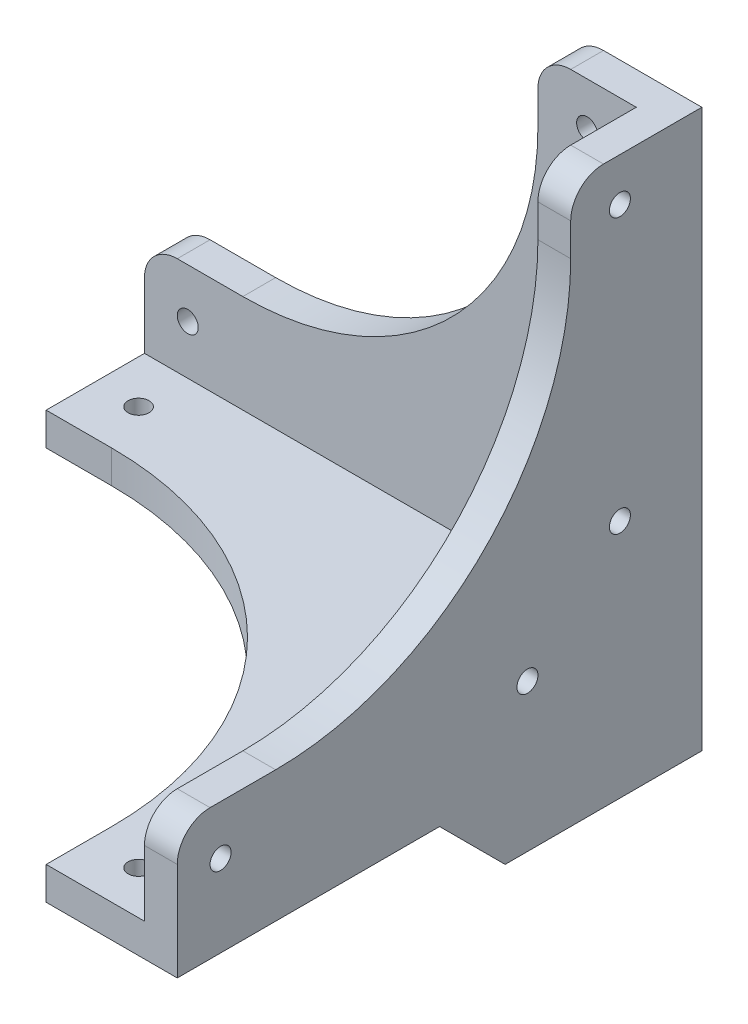
SolidWorks part; units mm, degrees
ref_plane "Front Plane" through (0, 0, 0) normal (0, 0, 1) x (1, 0, 0)
ref_plane "Top Plane" through (0, 0, 0) normal (0, 1, 0) x (1, 0, 0)
ref_plane "Right Plane" through (0, 0, 0) normal (1, 0, 0) x (0, 0, -1)
sketch "Sketch1" plane through (0, 0, 0) normal (0, 1, 0) x (1, 0, 0)
  line L1 (-50, 0) -> (-60, 0)
  line L3 (15, 15) -> (-60, 15)
  line L4 (-60, 0) -> (-60, 15)
  line L5 (-1037.2149, 7.5) -> (48962.7851, 7.5) construction
  line L6 (0, -50) -> (0, -60)
  line L7 (0, -60) -> (15, -60)
  line L8 (15, 15) -> (15, -60)
  line L9 (7.5, -1028.6065) -> (7.5, 48971.3935) construction
  arc A0 (-50, 0) -> (0, -50) centre (-50, -50) cw
  circle A1 centre (7.5, 7.5) radius 1.6
  circle A2 centre (7.5, -6.6) radius 1.6
  circle A3 centre (7.5, -53.4) radius 1.6
  circle A4 centre (-53.4, 7.5) radius 1.6
  circle A5 centre (-6.6, 7.5) radius 1.6
  point P14 (0, 0)
  dimension "D7" = 50
  dimension "D8" = 3.2
  dimension "D9" = 5
  dimension "D10" = 5
  dimension "D11" = 5
  dimension "D12" = 5
  dimension "D2" = 15
  dimension "D3" = 75
  dimension "D4" = 75
  dimension "D5" = 15
extrude "Boss-Extrude1" add sketch "Sketch1" along normal blind 5
sketch "Sketch2" plane through (15, 0, 0) normal (1, 0, 0) x (0, 0, -1)
  line L0 (-1069.6661, 12.5) -> (48930.3339, 12.5) construction
  line L1 (-60, 0) -> (15, 0) construction
  line L2 (-10, -10) -> (-20, 0)
  line L3 (-60, 5) -> (15, 5) construction
  line L4 (15, 5) -> (15, 0) construction
  line L5 (-10, -10) -> (15, -10)
  line L6 (-60, 0) -> (-60, 15)
  line L7 (5, 75) -> (15, 75)
  line L8 (15, -10) -> (15, 75)
  line L9 (-60, 5) -> (-60, 0) construction
  line L10 (-20, 0) -> (-60, 0)
  line L11 (7.5, -1006.2083) -> (7.5, 48993.7917) construction
  line L13 (-55, 20) -> (-45, 20)
  line L14 (0, 70) -> (0, 65)
  circle A0 centre (-53.4, 12.5) radius 1.6
  circle A1 centre (-6.6, 12.5) radius 1.6
  circle A2 centre (7.5, 26.6) radius 1.6
  circle A3 centre (7.5, 68.4) radius 1.6
  arc A4 (-60, 15) -> (-55, 20) centre (-55, 15) cw
  arc A5 (5, 75) -> (0, 70) centre (5, 70) ccw
  arc A6 (-45, 20) -> (0, 65) centre (-45, 65) ccw
  dimension "D8" = 3.2
  dimension "D9" = 5
  dimension "D10" = 5
  dimension "D11" = 5
  dimension "D12" = 5
  dimension "D13" = 5
  dimension "D4" = 5
  dimension "D14" = 45
  dimension "D1" = 10
  dimension "D2" = 70
  dimension "D3" = 15
  dimension "D5" = 15
  dimension "D6" = 25
  dimension "D7" = 45
extrude "Boss-Extrude2" add sketch "Sketch2" along normal blind 5
sketch "Sketch3" plane through (0, 0, -15) normal (0, 0, -1) x (-1, 0, 0)
  line L0 (-20, -10) -> (10, -10)
  line L1 (10, -10) -> (20, 0)
  line L2 (-15, 0) -> (60, 0) construction
  line L3 (20, 0) -> (60, 0)
  line L4 (60, 0) -> (60, 15)
  line L5 (55, 20) -> (45, 20)
  line L6 (0, 65) -> (0, 70)
  line L7 (-5, 75) -> (-20, 75)
  line L8 (-20, 75) -> (-20, -10)
  line L9 (-15, 5) -> (60, 5) construction
  line L10 (-15, 5) -> (-15, 75) construction
  line L11 (-1040.1164, 12.5) -> (48959.8836, 12.5) construction
  line L12 (-7.5, -917.74) -> (-7.5, 49082.26) construction
  arc A0 (60, 15) -> (55, 20) centre (55, 15) ccw
  arc A1 (0, 70) -> (-5, 75) centre (-5, 70) ccw
  arc A2 (45, 20) -> (0, 65) centre (45, 65) cw
  circle A3 centre (-7.5, 68.4) radius 1.6
  circle A4 centre (-7.5, 26.6) radius 1.6
  circle A5 centre (6.6, 12.5) radius 1.6
  circle A6 centre (53.4, 12.5) radius 1.6
  dimension "D5" = 5
  dimension "D6" = 45
  dimension "D7" = 3.2
  dimension "D8" = 5
  dimension "D9" = 5
  dimension "D10" = 5
  dimension "D11" = 5
  dimension "D1" = 30
  dimension "D2" = 45
  dimension "D3" = 15
  dimension "D4" = 15
extrude "Boss-Extrude3" add sketch "Sketch3" along normal blind 5
